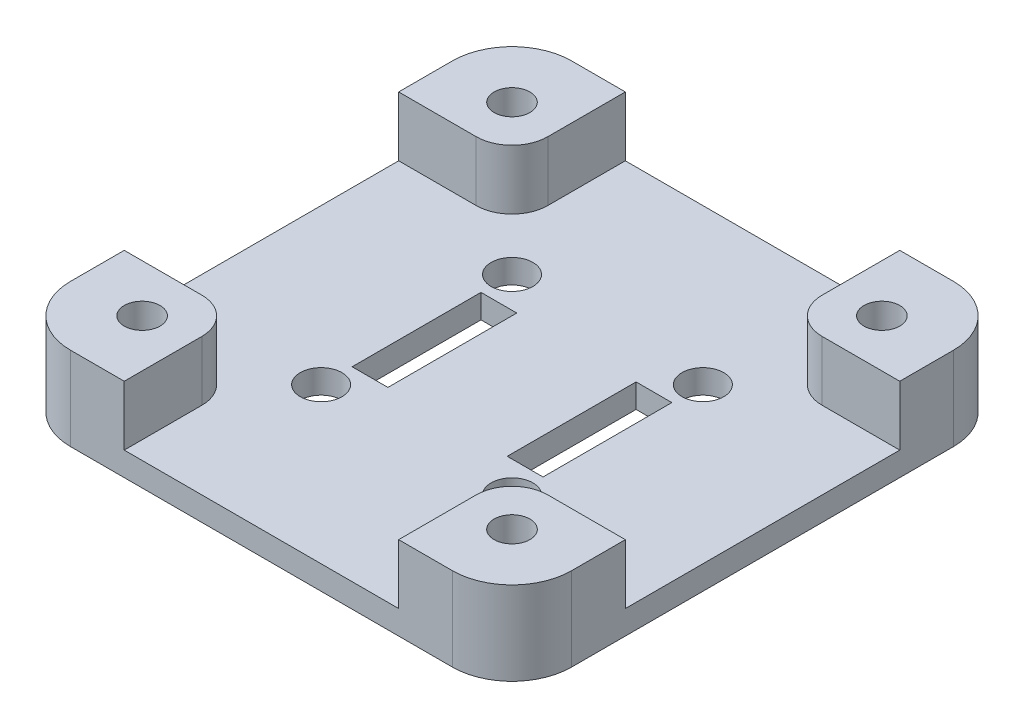
SolidWorks part; units mm, degrees
ref_plane "Front Plane" through (0, 0, 0) normal (0, 0, 1) x (1, 0, 0)
ref_plane "Top Plane" through (0, 0, 0) normal (0, 1, 0) x (1, 0, 0)
ref_plane "Right Plane" through (0, 0, 0) normal (1, 0, 0) x (0, 0, -1)
sketch "Sketch1" plane through (0, 0, 0) normal (0, 1, 0) x (1, 0, 0)
  line L1 (-21, 21) -> (21, 21)
  line L2 (-21, 21) -> (-21, -21)
  line L3 (-21, -21) -> (21, -21)
  line L4 (21, 21) -> (21, -21)
  line L5 (-21, 21) -> (21, -21) construction
  line L6 (-21, -21) -> (21, 21) construction
  line L7 (-15.5, 15.5) -> (15.5, 15.5) construction
  line L8 (-15.5, 15.5) -> (-15.5, -15.5) construction
  line L9 (-15.5, -15.5) -> (15.5, -15.5) construction
  line L10 (15.5, 15.5) -> (15.5, -15.5) construction
  line L11 (-15.5, 15.5) -> (15.5, -15.5) construction
  line L12 (-15.5, -15.5) -> (15.5, 15.5) construction
  circle A0 centre (-15.5, 15.5) radius 1.5
  circle A1 centre (15.5, 15.5) radius 1.5
  circle A2 centre (-15.5, -15.5) radius 1.5
  circle A3 centre (15.5, -15.5) radius 1.5
  point P0 (0, 0)
  point P5 (0, 0)
  dimension "D3" = 3
  dimension "D4" = 3
  dimension "D5" = 3
  dimension "D6" = 3
  dimension "D1" = 42
  dimension "D2" = 31
extrude "Boss-Extrude1" add sketch "Sketch1" along normal blind 7
sketch "Sketch2" plane through (0, 7, 0) normal (0, 1, 0) x (1, 0, 0)
  line L0 (-11.5, 11.5) -> (-11.5, 21)
  line L1 (-11.5, 11.5) -> (11.5, 11.5) construction
  line L2 (-11.5, 11.5) -> (-11.5, -11.5) construction
  line L3 (-11.5, -11.5) -> (11.5, -11.5) construction
  line L4 (11.5, 11.5) -> (11.5, -11.5) construction
  line L5 (-11.5, 11.5) -> (11.5, -11.5) construction
  line L6 (-11.5, -11.5) -> (11.5, 11.5) construction
  line L7 (21, 21) -> (-21, 21) construction
  line L8 (-11.5, 21) -> (11.5, 21)
  line L9 (11.5, 21) -> (11.5, 11.5)
  line L10 (11.5, 11.5) -> (21, 11.5)
  line L11 (21, -21) -> (21, 21) construction
  line L12 (21, 11.5) -> (21, -11.5)
  line L13 (21, -11.5) -> (11.5, -11.5)
  line L14 (11.5, -11.5) -> (11.5, -21)
  line L15 (-21, -21) -> (21, -21) construction
  line L16 (11.5, -21) -> (-11.5, -21)
  line L17 (-11.5, -21) -> (-11.5, -11.5)
  line L18 (-11.5, -11.5) -> (-21, -11.5)
  line L19 (-21, 21) -> (-21, -21) construction
  line L20 (-21, -11.5) -> (-21, 11.5)
  line L21 (-21, 11.5) -> (-11.5, 11.5)
  point P0 (0, 0)
  dimension "D1" = 23
extrude "Cut-Extrude1" cut sketch "Sketch2" against normal blind 5
sketch "Sketch4" plane through (0, 2, 0) normal (0, 1, 0) x (1, 0, 0)
  line L1 (-8, 8) -> (8, 8) construction
  line L2 (-8, 8) -> (-8, -8) construction
  line L3 (-8, -8) -> (8, -8) construction
  line L4 (8, 8) -> (8, -8) construction
  line L5 (-8, 8) -> (8, -8) construction
  line L6 (-8, -8) -> (8, 8) construction
  circle A0 centre (8, 8) radius 1.75
  circle A1 centre (8, -8) radius 1.75
  circle A2 centre (-8, -8) radius 1.75
  circle A3 centre (-8, 8) radius 1.75
  point P0 (0, 0)
  point P16 (0, 0)
  dimension "D2" = 3.5
  dimension "D1" = 16
  dimension "D3" = 4
extrude "Cut-Extrude3" cut sketch "Sketch4" against normal up to surface (2 mm away) up to face at (0, 0, 0)
sketch "Sketch5" plane through (0, 2, 0) normal (0, 1, 0) x (1, 0, 0)
  line L0 (0, 0) -> (6.5, 0) construction
  line L6 (0, -3.85) -> (0, 3.85) construction
  line L7 (5, 5.4) -> (8, 5.4)
  line L12 (5, 5.4) -> (5, -5.4)
  line L13 (5, -5.4) -> (8, -5.4)
  line L14 (8, 5.4) -> (8, -5.4)
  line L15 (5, 5.4) -> (8, -5.4) construction
  line L16 (5, -5.4) -> (8, 5.4) construction
  line L17 (-5, -5.4) -> (-8, -5.4)
  line L18 (-8, 5.4) -> (-8, -5.4)
  line L19 (-5, 5.4) -> (-8, 5.4)
  line L20 (-5, 5.4) -> (-5, -5.4)
  line L21 (-5, -5.4) -> (-8, 5.4) construction
  line L22 (-5, 5.4) -> (-8, -5.4) construction
  point P13 (-6.5, 0)
  dimension "D1" = 6.5
  dimension "D2" = 10.8
  dimension "D3" = 3
extrude "Cut-Extrude4" cut sketch "Sketch5" against normal blind 4
sketch "Sketch6" plane through (0, 0, 0) normal (0, -1, 0) x (1, 0, 0)
  circle A0 centre (-15.5, 15.5) radius 3
  circle A1 centre (15.5, 15.5) radius 3
  circle A2 centre (15.5, -15.5) radius 3
  circle A3 centre (-15.5, -15.5) radius 3
  dimension "D1" = 6
  dimension "D2" = 6
  dimension "D3" = 6
  dimension "D4" = 6
extrude "Cut-Extrude5" cut sketch "Sketch6" against normal blind 3
fillet "Fillet1" radius 5 4 edges at (-21, 3.5, -21) (21, 3.5, -21) (21, 3.5, 21) (-21, 3.5, 21)
fillet "Fillet2" radius 3 4 edges at (11.5, 4.5, -11.5) (11.5, 4.5, 11.5) (-11.5, 4.5, -11.5) (-11.5, 4.5, 11.5)
